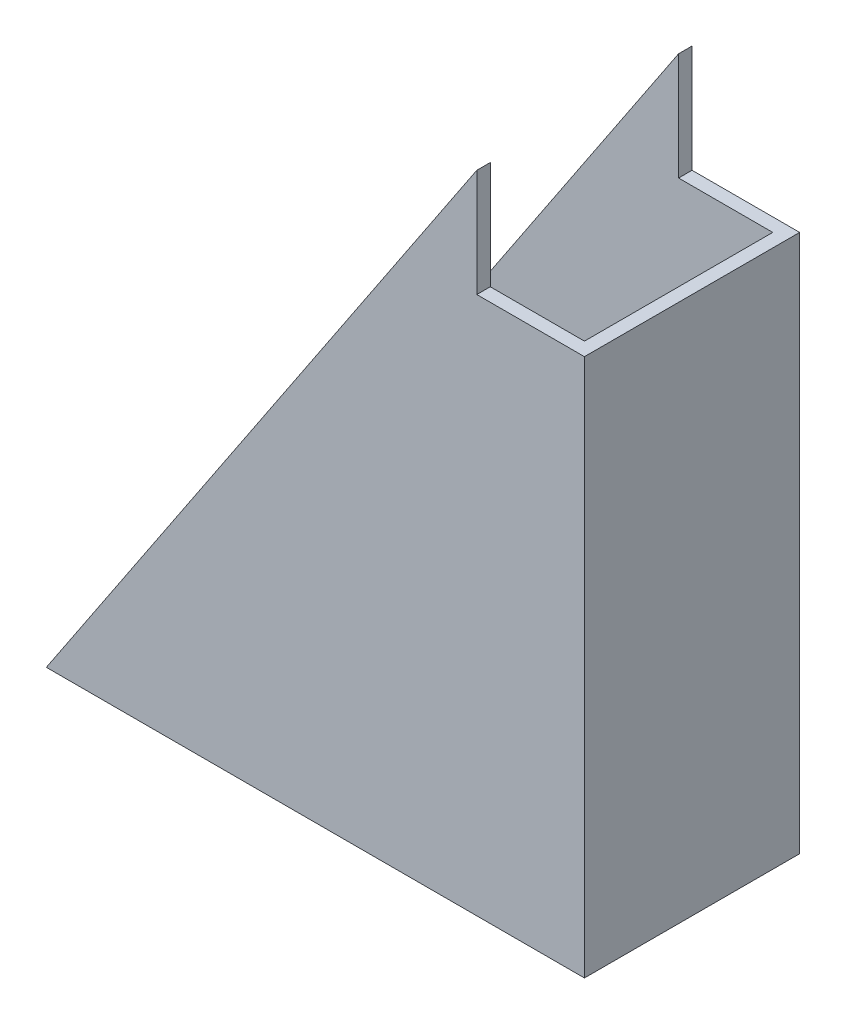
SolidWorks part; units mm, degrees
material "6061-T6 (SS)"
ref_plane "Front Plane" through (0, 0, 0) normal (0, 0, 1) x (1, 0, 0)
ref_plane "Top Plane" through (0, 0, 0) normal (0, 1, 0) x (1, 0, 0)
ref_plane "Right Plane" through (0, 0, 0) normal (1, 0, 0) x (0, 0, -1)
ref_plane "Plane1" through (0, 25.4, 0) normal (0, 1, 0) x (1, 0, 0)
sketch "Sketch1" plane through (0, 25.4, 0) normal (0, 1, 0) x (1, 0, 0)
  line L0 (266.7, -381) -> (330.2, -381) construction
  line L1 (330.2, -381) -> (330.2, -355.6) construction
  line L2 (266.7, -355.6) -> (330.2, -355.6) construction
  line L3 (266.7, -381) -> (266.7, -355.6) construction
  line L4 (266.7, -381) -> (330.2, -381)
  line L5 (330.2, -381) -> (330.2, -355.6)
  line L6 (266.7, -355.6) -> (330.2, -355.6)
  line L7 (266.7, -381) -> (266.7, -355.6)
  line L8 (268.2875, -357.1875) -> (328.6125, -357.1875)
  line L9 (328.6125, -379.4125) -> (328.6125, -357.1875)
  line L10 (268.2875, -379.4125) -> (328.6125, -379.4125)
  line L11 (268.2875, -379.4125) -> (268.2875, -357.1875)
  dimension "D1" = 1.5875
extrude "Boss-Extrude1" add sketch "Sketch1" along normal up to vertex (76.2 mm away)
sketch "Sketch2" plane through (0, 0, 0) normal (0, 0, 1) x (1, 0, 0)
  line L0 (317.5, 101.6) -> (266.7, 25.4)
  line L2 (330.2, 101.6) -> (317.5, 101.6) construction
  line L3 (330.2, 88.9) -> (317.5, 88.9) construction
  line L4 (317.5, 101.6) -> (317.5, 88.9) construction
  line L5 (330.2, 101.6) -> (330.2, 88.9) construction
  line L6 (330.2, 88.9) -> (317.5, 88.9)
  line L7 (317.5, 101.6) -> (317.5, 88.9)
  line L8 (330.2, 101.6) -> (317.5, 101.6)
  line L9 (330.2, 101.6) -> (330.2, 88.9)
  line L10 (266.7, 25.4) -> (266.7, 101.6)
  line L11 (266.7, 101.6) -> (317.5, 101.6)
extrude "Cut-Extrude1" cut sketch "Sketch2" along normal through all contours L11 L10 L0 | L9 L8 L7 L6
